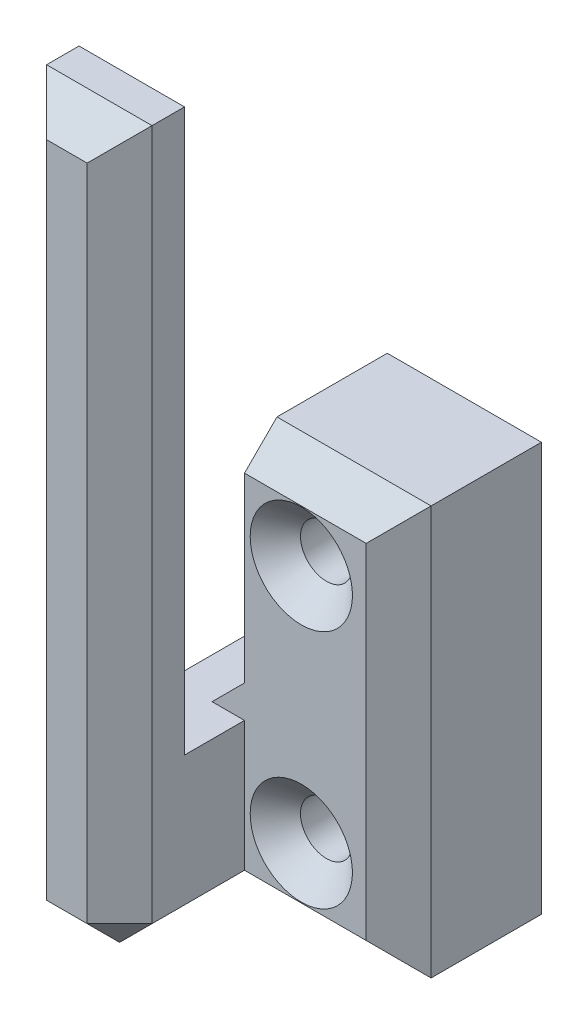
SolidWorks part; units mm, degrees
ref_plane "Front Plane" through (0, 0, 0) normal (0, 0, 1) x (1, 0, 0)
ref_plane "Top Plane" through (0, 0, 0) normal (0, 1, 0) x (1, 0, 0)
ref_plane "Right Plane" through (0, 0, 0) normal (1, 0, 0) x (0, 0, -1)
sketch "Sketch1" plane through (0, 0, 0) normal (0, 0, 1) x (1, 0, 0)
  line L0 (0, 12.6) -> (8, 12.6) construction
  line L1 (0, 0) -> (8, 0)
  line L2 (0, 0) -> (0, 25.2)
  line L3 (0, 25.2) -> (8, 25.2)
  line L5 (4, 25.2) -> (4, 0) construction
  line L6 (3.5, 25.2) -> (3.5, 0) construction
  line L8 (8, 0) -> (9.5, 0)
  line L10 (8, 25.2) -> (9.5, 25.2)
  line L11 (9.5, 0) -> (9.5, 25.2)
  circle A0 centre (3.5, 20) radius 1.6
  circle A1 centre (3.5, 5.2) radius 1.6
  dimension "D4" = 3.2
  dimension "D1" = 25.2
  dimension "D2" = 9.5
  dimension "D3" = 3.5
  dimension "D5" = 7.4
extrude "Boss-Extrude1" add sketch "Sketch1" along normal blind 8.8
sketch "Sketch2" plane through (0, 0, 8.8) normal (0, 0, 1) x (1, 0, 0)
  line L0 (9.5, 0) -> (9.5, 25.2) construction
  line L1 (9.5, 0) -> (16, 0)
  line L2 (9.5, 0) -> (9.5, 10)
  line L3 (9.5, 10) -> (16, 10)
  line L4 (16, 0) -> (16, 10)
  dimension "D1" = 6.5
  dimension "D2" = 10
extrude "Boss-Extrude2" add sketch "Sketch2" along normal blind 3.7 and the other way up to surface other way up to face at (5.1, 20, 0)
sketch "Sketch3" plane through (0, 0, 12.5) normal (0, 0, 1) x (1, 0, 0)
  line L0 (16, 0) -> (16, 10) construction
  line L1 (9.5, 0) -> (16, 0)
  line L2 (9.5, 0) -> (9.5, 44.6)
  line L3 (9.5, 44.6) -> (16, 44.6)
  line L4 (16, 0) -> (16, 44.6)
  line L5 (9.5, 25.2) -> (0, 25.2) construction
  point P9 (4.75, 25.2)
  dimension "D1" = 19.4
extrude "Boss-Extrude3" add sketch "Sketch3" along normal blind 4
ref_plane "Plane1" through (4.75, 0, 0) normal (1, 0, 0) x (0, 0, -1)
mirror "Mirror1" about plane through (4.75, 0, 0) normal (1, 0, 0) of "Boss-Extrude2", "Boss-Extrude3"
sketch "Sketch4" plane through (0, 0, 16.5) normal (0, 0, 1) x (1, 0, 0)
  line L4 (9.5, 44.6) -> (9.5, 0)
  line L5 (9.5, 0) -> (16, 0)
  line L6 (16, 0) -> (16, 44.6)
  line L7 (16, 44.6) -> (9.5, 44.6)
  line L8 (9.5, 44.6) -> (9.5, 0)
  line L9 (9.5, 0) -> (16, 0)
  line L10 (16, 0) -> (16, 44.6)
  line L11 (16, 44.6) -> (9.5, 44.6)
  dimension "D1" = 0
extrude "Cut-Extrude1" cut sketch "Sketch4" against normal through all
chamfer "Chamfer2" distance 2 angle 45 11 edges at (9.5, 12.6, 8.8) (4.75, 25.2, 8.8) (0, 10, 4.4) (0, 0, 12.65) (-6.5, 0, 8.25) (-6.5, 10, 6.25) (0, 22.3, 16.5) (-3.25, 44.6, 16.5) (-6.5, 22.3, 16.5) (-3.25, 0, 16.5) (4.75, 0, 8.8)
chamfer "Chamfer3" distance 1.55 angle 45 2 edges at (1.9, 5.2, 8.8) (5.1, 20, 8.8)
